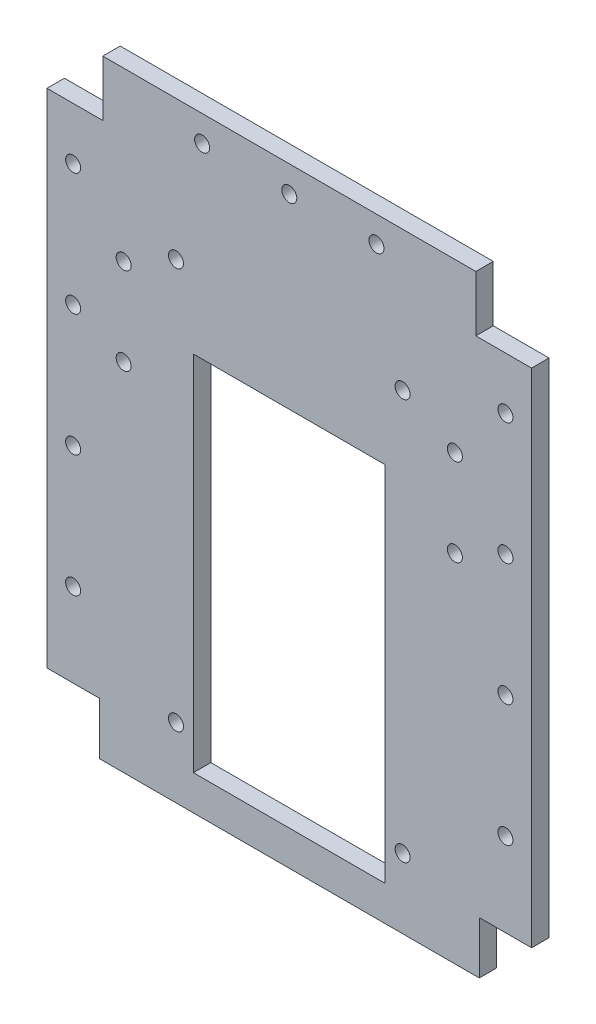
SolidWorks part; units mm, degrees
ref_plane "Front Plane" through (0, 0, 0) normal (0, 0, 1) x (1, 0, 0)
ref_plane "Top Plane" through (0, 0, 0) normal (0, 1, 0) x (1, 0, 0)
ref_plane "Right Plane" through (0, 0, 0) normal (1, 0, 0) x (0, 0, -1)
sketch "Sketch1" plane through (0, 0, 0) normal (0, 0, 1) x (1, 0, 0)
  line L1 (0, 0) -> (139, 0)
  line L2 (0, 0) -> (0, 160)
  line L3 (0, 160) -> (139, 160)
  line L4 (139, 0) -> (139, 160)
  dimension "D1" = 139
  dimension "D2" = 160
extrude "Boss-Extrude1" add sketch "Sketch1" along normal blind 5
sketch "Sketch2" plane through (0, 0, 5) normal (0, 0, 1) x (1, 0, 0)
  line L0 (69.5, 160) -> (69.5, 0) construction
  line L5 (139, 160) -> (0, 160) construction
  line L6 (0, 0) -> (139, 0) construction
  line L7 (0, 80) -> (139, 80) construction
  line L8 (0, 160) -> (0, 0) construction
  line L9 (139, 0) -> (139, 160) construction
  line L14 (139, 160) -> (123, 160)
  line L15 (139, 160) -> (139, 144)
  line L16 (139, 144) -> (123, 144)
  line L17 (123, 160) -> (123, 144)
  line L18 (16, 160) -> (16, 144)
  line L19 (0, 144) -> (16, 144)
  line L20 (0, 160) -> (0, 144)
  line L21 (0, 160) -> (16, 160)
  dimension "D1" = 16
  dimension "D2" = 16
  dimension "D3" = 16
  dimension "D4" = 16
extrude "Cut-Extrude1" cut sketch "Sketch2" against normal blind 5
sketch "Sketch3" plane through (0, 0, 5) normal (0, 0, 1) x (1, 0, 0)
  line L0 (69.5, 160) -> (69.5, 0) construction
  line L1 (123, 160) -> (16, 160) construction
  line L2 (0, 0) -> (139, 0) construction
  circle A0 centre (69.5, 152.5) radius 2.15
  circle A1 centre (44.5, 152.5) radius 2.15
  circle A3 centre (94.5, 152.5) radius 2.15
  dimension "D1" = 4.3
  dimension "D5" = 4.3
  dimension "D2" = 7.5
  dimension "D3" = 7.5
  dimension "D4" = 25
extrude "Cut-Extrude2" cut sketch "Sketch3" against normal blind 5
sketch "Sketch4" plane through (0, 0, 5) normal (0, 0, 1) x (1, 0, 0)
  line L0 (123, 144) -> (139, 144) construction
  line L1 (139, 0) -> (139, 144) construction
  line L2 (69.5, 160) -> (69.5, 0) construction
  line L3 (123, 160) -> (16, 160) construction
  line L4 (0, 0) -> (139, 0) construction
  circle A0 centre (131.5, 129) radius 2.15
  circle A1 centre (7.5, 129) radius 2.15
  dimension "D1" = 4.3
  dimension "D2" = 15
  dimension "D3" = 7.5
extrude "Cut-Extrude3" cut sketch "Sketch4" against normal blind 5
pattern_linear "LPattern1" count 4 spacing 35 along (0, -1, 0) of "Cut-Extrude3"
sketch "Sketch5" plane through (0, 0, 5) normal (0, 0, 1) x (1, 0, 0)
  line L0 (123, 160) -> (16, 160) construction
  line L1 (69.5, 160) -> (69.5, 0) construction
  line L2 (0, 0) -> (139, 0) construction
  circle A0 centre (117, 112) radius 2.15
  circle A1 centre (117, 87) radius 2.15
  circle A2 centre (22, 87) radius 2.15
  circle A3 centre (22, 112) radius 2.15
  dimension "D1" = 4.3
  dimension "D2" = 4.3
  dimension "D3" = 48
  dimension "D4" = 25
  dimension "D5" = 47.5
  dimension "D6" = 47.5
extrude "Cut-Extrude4" cut sketch "Sketch5" against normal blind 5
sketch "Sketch6" plane through (0, 0, 0) normal (0, 0, -1) x (-1, 0, 0)
  line L0 (0, 0) -> (-139, 0) construction
  line L1 (-124, 0) -> (-15, 0)
  line L2 (-124, 0) -> (-124, -15)
  line L3 (-124, -15) -> (-15, -15)
  line L4 (-15, 0) -> (-15, -15)
  line L5 (-139, 0) -> (-139, 144) construction
  line L6 (0, 144) -> (0, 0) construction
  dimension "D1" = 15
  dimension "D2" = 15
  dimension "D3" = 15
extrude "Boss-Extrude2" add sketch "Sketch6" against normal blind 5
sketch "Sketch7" plane through (0, 0, 5) normal (0, 0, 1) x (1, 0, 0)
  line L0 (124, -15) -> (15, -15) construction
  line L1 (42, -5) -> (97, -5)
  line L2 (42, -5) -> (42, 99)
  line L3 (42, 99) -> (97, 99)
  line L4 (97, -5) -> (97, 99)
  line L5 (69.5, 160) -> (69.5, -15) construction
  line L6 (123, 160) -> (16, 160) construction
  dimension "D1" = 104
  dimension "D2" = 55
  dimension "D3" = 10
  dimension "D4" = 27.5
extrude "Cut-Extrude5" cut sketch "Sketch7" against normal blind 5
sketch "Sketch8" plane through (0, 0, 5) normal (0, 0, 1) x (1, 0, 0)
  line L0 (124, -15) -> (15, -15) construction
  line L1 (97, -5) -> (97, 99) construction
  line L2 (69.5, 160) -> (69.5, -15) construction
  line L3 (123, 160) -> (16, 160) construction
  circle A0 centre (102, 5) radius 2.15
  circle A1 centre (102, 120) radius 2.15
  circle A2 centre (37, 120) radius 2.15
  circle A3 centre (37, 5) radius 2.15
  dimension "D1" = 4.3
  dimension "D2" = 20
  dimension "D4" = 4.3
  dimension "D3" = 5
  dimension "D5" = 115
extrude "Cut-Extrude6" cut sketch "Sketch8" against normal blind 5
